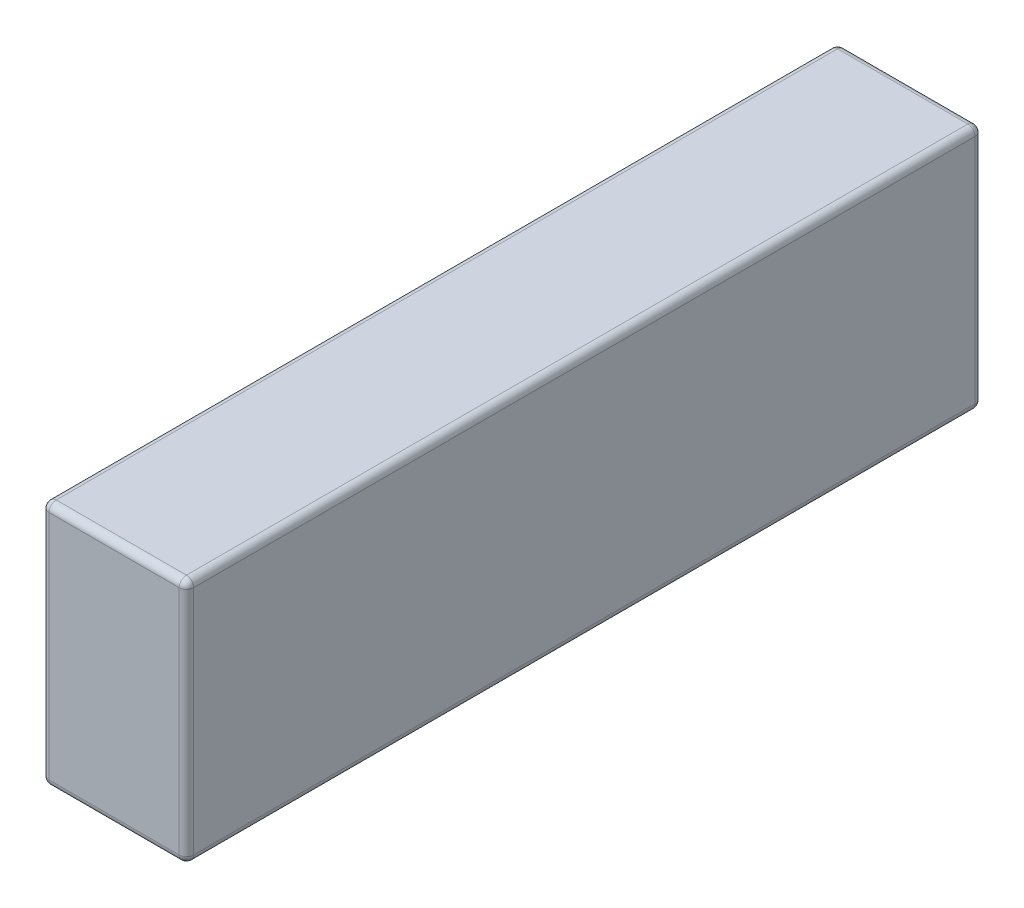
SolidWorks part; units mm, degrees
ref_plane "Front Plane" through (0, 0, 0) normal (0, 0, 1) x (1, 0, 0)
ref_plane "Top Plane" through (0, 0, 0) normal (0, 1, 0) x (1, 0, 0)
ref_plane "Right Plane" through (0, 0, 0) normal (1, 0, 0) x (0, 0, -1)
sketch "Sketch1" plane through (0, 0, 0) normal (0, 1, 0) x (1, 0, 0)
  line L1 (5, -59.5536) -> (-15, -59.5536)
  line L2 (5, -59.5536) -> (5, 50.4464)
  line L3 (5, 50.4464) -> (-15, 50.4464)
  line L4 (-15, -59.5536) -> (-15, 50.4464)
  line L5 (5, -59.5536) -> (-15, 50.4464) construction
  line L6 (5, 50.4464) -> (-15, -59.5536) construction
  point P0 (-5, -4.5536)
  dimension "D1" = 20
  dimension "D2" = 110
extrude "Boss-Extrude1" add sketch "Sketch1" along normal blind 34
fillet "Fillet1" radius 1 12 edges at (-5, 0, -50.4464) (-15, 17, -50.4464) (-15, 0, 4.5536) (-15, 17, 59.5536) (-5, 0, 59.5536) (-5, 34, -50.4464) (-5, 34, 59.5536) (-15, 34, 4.5536) (5, 17, 59.5536) (5, 34, 4.5536) (5, 17, -50.4464) (5, 0, 4.5536)
